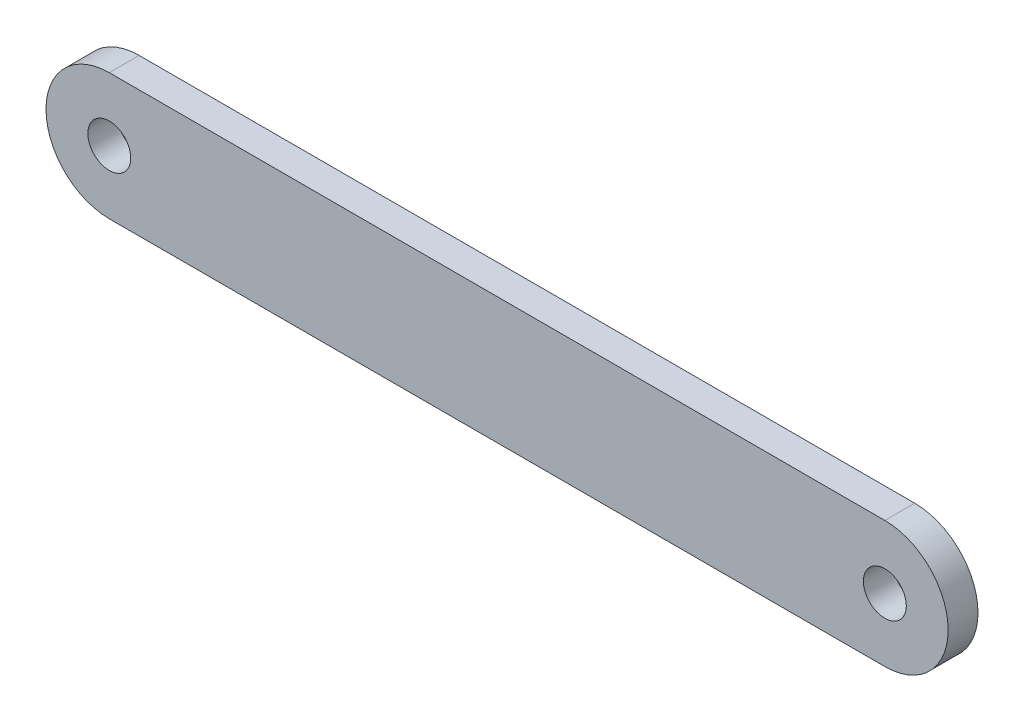
SolidWorks part; units mm, degrees
material "Custom Plastic"
ref_plane "Front Plane" through (0, 0, 0) normal (0, 0, 1) x (1, 0, 0)
ref_plane "Top Plane" through (0, 0, 0) normal (0, 1, 0) x (1, 0, 0)
ref_plane "Right Plane" through (0, 0, 0) normal (1, 0, 0) x (0, 0, -1)
sketch "Sketch1" plane through (0, 0, 0) normal (0, 0, 1) x (1, 0, 0)
  line L0 (-38.9128, 0) -> (38.9128, 0) construction
  line L1 (-38.9128, 6.35) -> (38.9128, 6.35)
  line L2 (-38.9128, -6.35) -> (38.9128, -6.35)
  arc A0 (-38.9128, 6.35) -> (-38.9128, -6.35) centre (-38.9128, 0) ccw
  arc A1 (38.9128, -6.35) -> (38.9128, 6.35) centre (38.9128, 0) ccw
  point P3 (0, 0)
  dimension "D1" = 6.35
  dimension "D2" = 77.8256
extrude "Boss-Extrude1" add sketch "Sketch1" along normal blind 2.9972
hole_wizard "#8 Clearance Hole1" positions "Sketch3" profile "Sketch2" hole size "#8" standard "ANSI Inch"
sketch "Sketch3" plane through (0, 0, 2.9972) normal (0, 0, 1) x (1, 0, 0)
  point P0 (-38.9128, 0)
  point P3 (38.9128, 0)
sketch "Sketch2" plane through (-38.9128, 0, 2.9972) normal (1, 0, 0) x (0, -1, 0)
  line L0 (0, 0) -> (0, 6.351)
  line L1 (0, 6.351) -> (2.1526, 6.351)
  line L2 (2.1526, 6.351) -> (2.1526, 0)
  line L5 (2.1526, 0) -> (0, 0)
  line L10 (0, 6.351) -> (-2.1526, 6.351) construction
  line L11 (0, -6.35) -> (0, 107.95) construction
  dimension "Hole Dia." = 4.3053
  dimension "Hole Depth" = 6.351
  dimension "Drill Angle" = 180
sketch "Sketch4" plane through (0, 0, 0) normal (0, 0, -1) x (-1, 0, 0)
  line L0 (-31.082, 6.35) -> (-27.157, 24.9913)
  line L1 (-38.9128, 6.35) -> (38.9128, 6.35) construction
  line L2 (-27.157, 24.9913) -> (7.018, 6.35)
  line L3 (-31.082, 6.35) -> (7.018, 6.35)
  circle A0 centre (-38.9128, 0) radius 2.1526 construction
  dimension "D1" = 19.05
  dimension "D2" = 38.1
  dimension "D3" = 78.11
  dimension "D4" = 7.8308
extrude "hard stop" [suppressed] add sketch "Sketch4" against normal blind 2.9972
